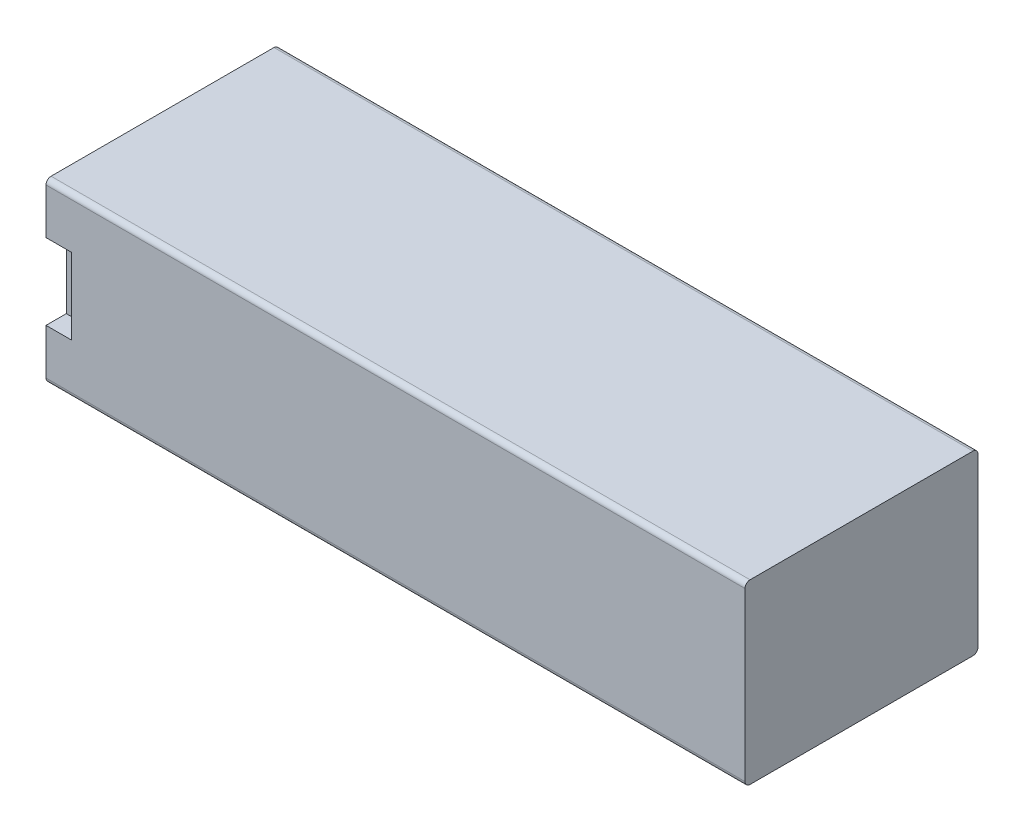
SolidWorks part; units mm, degrees
ref_plane "Front Plane" through (0, 0, 0) normal (0, 0, 1) x (1, 0, 0)
ref_plane "Top Plane" through (0, 0, 0) normal (0, 1, 0) x (1, 0, 0)
ref_plane "Right Plane" through (0, 0, 0) normal (1, 0, 0) x (0, 0, -1)
sketch "Sketch1" plane through (0, 0, 0) normal (0, 0, 1) x (1, 0, 0)
  line L1 (0, 0) -> (138, 0)
  line L2 (0, 0) -> (0, 35)
  line L3 (0, 35) -> (138, 35)
  line L4 (138, 0) -> (138, 35)
  dimension "D1" = 138
  dimension "D2" = 35
extrude "Boss-Extrude1" add sketch "Sketch1" against normal blind 46
fillet "Fillet2" radius 1 4 edges at (69, 0, -46) (69, 0, 0) (69, 35, -46) (69, 35, 0)
sketch "Sketch4" plane through (0, 0, 0) normal (-1, 0, 0) x (0, 0, 1)
  line L0 (0, 34) -> (0, 1) construction
  line L1 (0, 25) -> (-4, 25)
  line L2 (0, 25) -> (0, 10)
  line L3 (0, 10) -> (-4, 10)
  line L4 (-4, 25) -> (-4, 10)
  point P8 (0, 17.5)
  point P9 (0, 17.5)
  dimension "D1" = 15
  dimension "D2" = 4
extrude "Cut-Extrude2" cut sketch "Sketch4" against normal blind 5
fillet "Fillet3" radius 2 1 edges at (5, 17.5, -4)
